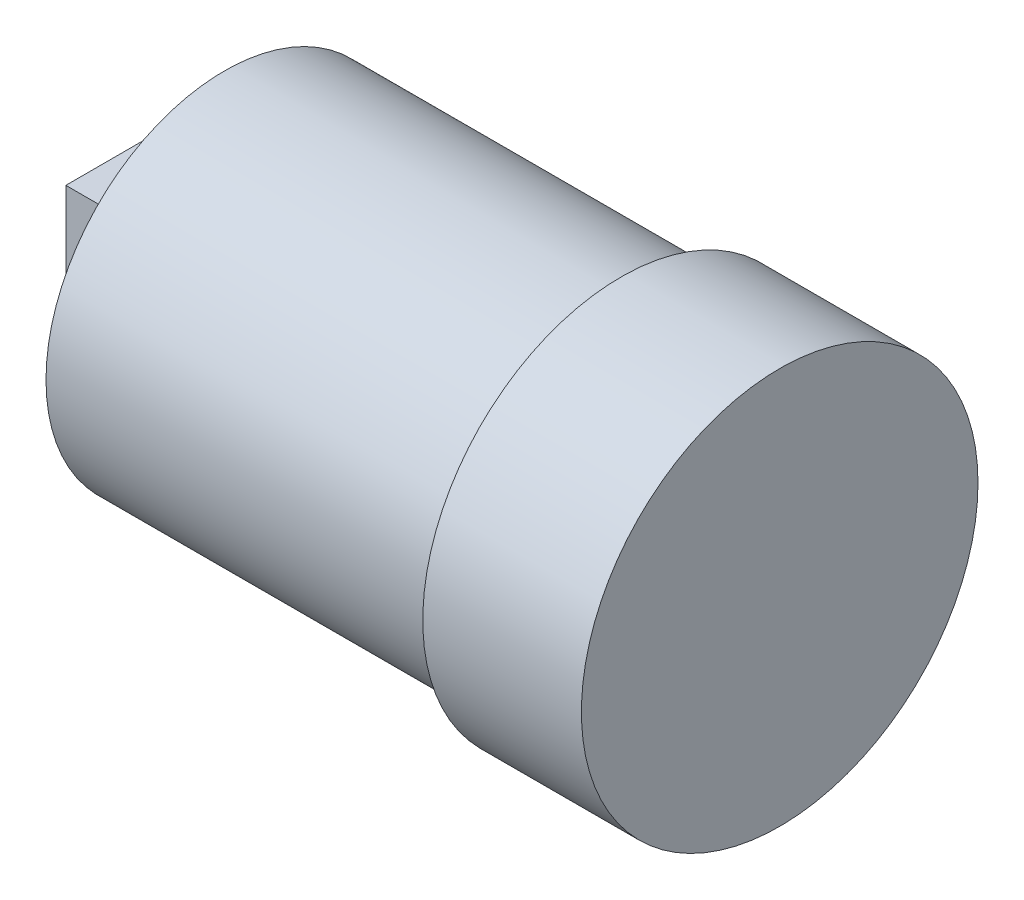
SolidWorks part; units mm, degrees
ref_plane "前视基准面" through (0, 0, 0) normal (0, 0, 1) x (1, 0, 0)
ref_plane "上视基准面" through (0, 0, 0) normal (0, 1, 0) x (1, 0, 0)
ref_plane "右视基准面" through (0, 0, 0) normal (1, 0, 0) x (0, 0, -1)
other "Configuration Table"
sketch "草图1" plane through (0, 0, 0) normal (1, 0, 0) x (0, 0, -1)
  circle A0 centre (0, 0) radius 25
  dimension "D1" = 50
extrude "凸台-拉伸1" add sketch "草图1" along normal blind 20
sketch "草图2" plane through (0, 0, 0) normal (-1, 0, 0) x (0, 0, 1)
  line L1 (-10, -10) -> (10, -10)
  line L2 (-10, -10) -> (-10, 10)
  line L3 (-10, 10) -> (10, 10)
  line L4 (10, -10) -> (10, 10)
  line L5 (-10, -10) -> (10, 10) construction
  line L6 (-10, 10) -> (10, -10) construction
  point P0 (0, 0)
  dimension "D1" = 20
  dimension "D2" = 20
extrude "凸台-拉伸2" add sketch "草图2" along normal blind 60
sketch "草图3" plane through (0, 0, 0) normal (-1, 0, 0) x (0, 0, 1)
  circle A0 centre (0, 0) radius 22.5
  dimension "D1" = 45
extrude "凸台-拉伸3" add sketch "草图3" along normal blind 50
